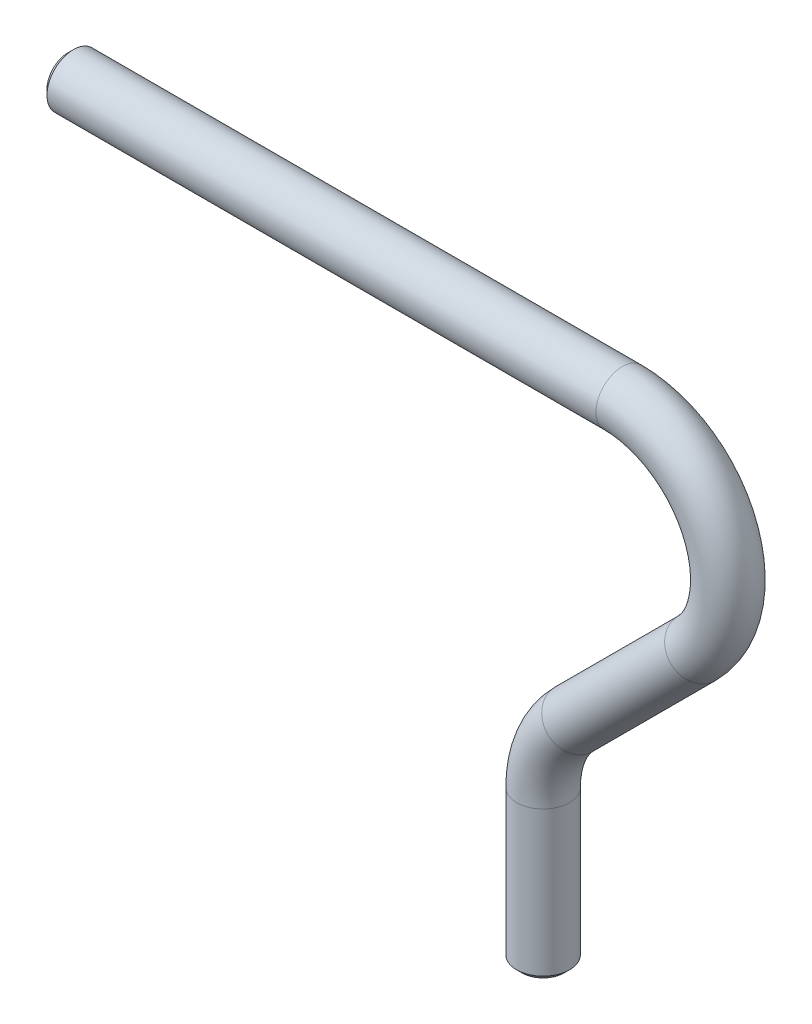
SolidWorks part; units mm, degrees
ref_plane "Спереди" through (0, 0, 0) normal (0, 0, 1) x (1, 0, 0)
ref_plane "Сверху" through (0, 0, 0) normal (0, 1, 0) x (1, 0, 0)
ref_plane "Справа" through (0, 0, 0) normal (1, 0, 0) x (0, 0, -1)
other "Configuration Table"
sketch "Эскиз1" plane through (0, 0, 0) normal (0, 0, 1) x (1, 0, 0)
  line L0 (0, 0) -> (105, 0)
  line L1 (119.1421, -34.1421) -> (95.8579, -57.4264)
  line L2 (90, -71.5685) -> (90, -100)
  arc A0 (105, 0) -> (119.1421, -34.1421) centre (105, -20) cw
  arc A1 (95.8579, -57.4264) -> (90, -71.5685) centre (110, -71.5685) ccw
  point P9 (0, 0)
  point P12 (0, 0)
  dimension "D2" = 20
  dimension "D5" = 20
  dimension "D1" = 125
  dimension "D3" = 100
  dimension "D4" = 45
  dimension "D6" = 90
sketch "Эскиз2" plane through (0, 0, 0) normal (1, 0, 0) x (0, 0, -1)
  circle A0 centre (0, 0) radius 5
  circle A1 centre (0, 0) radius 3
  dimension "D1" = 10
  dimension "D2" = 6
sweep "По траектории1" add profiles "Эскиз2" path "Эскиз1"
cosmetic thread "Условное изображение резьбы1" parameters "D1"=11, "D2"=8.344
cosmetic thread "Условное изображение резьбы2" parameters "D1"=11, "D2"=8.344
chamfer "Фаска1" distance 1 angle 45 2 edges at (0, 0, -5) (90, -100, -5)
